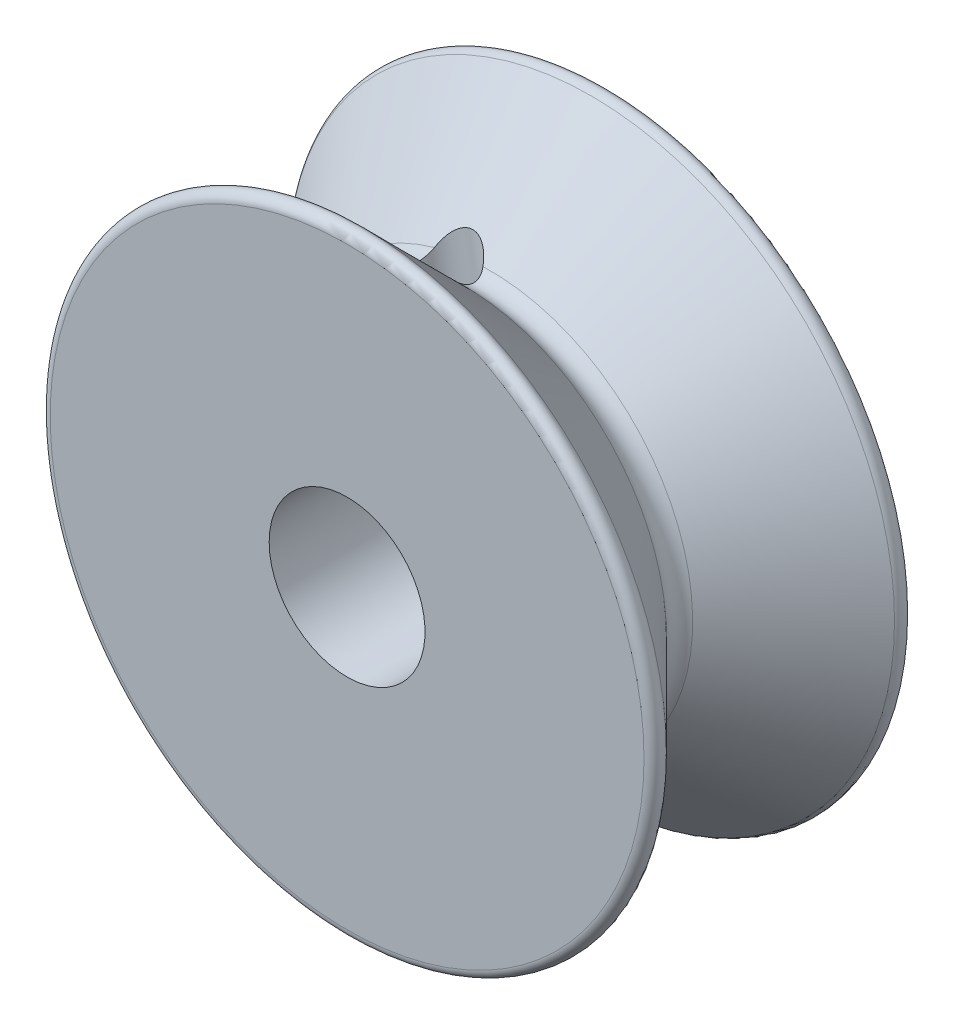
SolidWorks part; units mm, degrees
ref_plane "Front Plane" through (0, 0, 0) normal (0, 0, 1) x (1, 0, 0)
ref_plane "Top Plane" through (0, 0, 0) normal (0, 1, 0) x (1, 0, 0)
ref_plane "Right Plane" through (0, 0, 0) normal (1, 0, 0) x (0, 0, -1)
sketch "Sketch2" plane through (0, 0, 0) normal (0, 0, 1) x (1, 0, 0)
  line L0 (-0.3676, 7.7711) -> (0.0065, 8.0211)
  line L1 (0.0065, 8.0211) -> (0.3676, 7.7711)
  line L2 (0.3676, 7.7711) -> (0.8007, 7.8932)
  line L3 (0.8007, 7.8932) -> (1.0669, 7.5439)
  line L4 (1.0669, 7.5439) -> (1.5165, 7.5262)
  line L5 (1.5165, 7.5262) -> (1.6617, 7.1117)
  line L6 (1.6617, 7.1117) -> (2.0839, 6.956)
  line L7 (2.0839, 6.956) -> (2.0939, 6.5169)
  line L8 (2.0939, 6.5169) -> (2.4472, 6.2383)
  line L9 (2.4472, 6.2383) -> (2.3211, 5.8176)
  line L10 (2.3211, 5.8176) -> (2.5711, 5.4435)
  line L11 (2.5711, 5.4435) -> (2.3211, 5.0824)
  line L12 (2.3211, 5.0824) -> (2.4432, 4.6493)
  line L13 (2.4432, 4.6493) -> (2.0939, 4.3831)
  line L14 (2.0939, 4.3831) -> (2.0762, 3.9335)
  line L15 (2.0762, 3.9335) -> (1.6617, 3.7883)
  line L16 (1.6617, 3.7883) -> (1.506, 3.3661)
  line L17 (1.506, 3.3661) -> (1.0669, 3.3561)
  line L18 (1.0669, 3.3561) -> (0.7883, 3.0028)
  line L19 (0.7883, 3.0028) -> (0.3676, 3.1289)
  line L20 (0.3676, 3.1289) -> (-0.0065, 2.8789)
  line L21 (-0.0065, 2.8789) -> (-0.3676, 3.1289)
  line L22 (-0.3676, 3.1289) -> (-0.8007, 3.0068)
  line L23 (-0.8007, 3.0068) -> (-1.0669, 3.3561)
  line L24 (-1.0669, 3.3561) -> (-1.5165, 3.3738)
  line L25 (-1.5165, 3.3738) -> (-1.6617, 3.7883)
  line L26 (-1.6617, 3.7883) -> (-2.0839, 3.944)
  line L27 (-2.0839, 3.944) -> (-2.0939, 4.3831)
  line L28 (-2.0939, 4.3831) -> (-2.4472, 4.6617)
  line L29 (-2.4472, 4.6617) -> (-2.3211, 5.0824)
  line L30 (-2.3211, 5.0824) -> (-2.5711, 5.4565)
  line L31 (-2.5711, 5.4565) -> (-2.3211, 5.8176)
  line L32 (-2.3211, 5.8176) -> (-2.4432, 6.2507)
  line L33 (-2.4432, 6.2507) -> (-2.0939, 6.5169)
  line L34 (-2.0939, 6.5169) -> (-2.0762, 6.9665)
  line L35 (-2.0762, 6.9665) -> (-1.6617, 7.1117)
  line L36 (-1.6617, 7.1117) -> (-1.506, 7.5339)
  line L37 (-1.506, 7.5339) -> (-1.0669, 7.5439)
  line L38 (-1.0669, 7.5439) -> (-0.7883, 7.8972)
  line L39 (-0.7883, 7.8972) -> (-0.3676, 7.7711)
  line L40 (-0.3676, 7.7711) -> (0.3676, 7.7711) construction
  circle A1 centre (0, 5.45) radius 4
  circle A2 centre (0, 5.45) radius 2.35 construction
  point P68 (0, 5.45)
  dimension "D2" = 8
  dimension "D3" = 4.7
  dimension "D4" = 0.25
  dimension "D5" = 0.4392
  dimension "D6" = 5.1421
  dimension "D1" = 20
extrude "Boss-Extrude1" add sketch "Sketch2" against normal up to surface (2.9 mm away)
sketch "Sketch3" plane through (0, 0, 0) normal (0, 0, 1) x (1, 0, 0)
  circle A0 centre (0, 5.45) radius 3
  circle A1 centre (0, 5.45) radius 1.2
  dimension "D1" = 2.4
extrude "Boss-Extrude2" add sketch "Sketch3" along normal blind 2
ref_axis "Axis1" through (0, 5.45, 2) along (0, 0, -1)
ref_plane "Plane1" through (-0.8421, 5.3166, 0) normal (-0.1564, 0.9877, 0) x (0.9877, 0.1564, 0)
sketch "Sketch4" plane through (-0.8421, 5.3166, 0) normal (-0.1564, 0.9877, 0) x (0.9877, 0.1564, 0)
  line L0 (-3.1474, 1.6) -> (-7.1474, 1.6)
  line L1 (4.8526, 2.9) -> (-3.1474, 2.9) construction
  line L2 (-7.3242, 1.1732) -> (-4.6045, -1.5464)
  line L3 (-4.6045, -2.2536) -> (-7.3242, -4.9732)
  line L4 (-7.1474, -5.4) -> (-3.1474, -5.4)
  line L5 (-3.1474, -5.4) -> (-3.1474, 1.6)
  line L6 (-3.1474, 2.9) -> (-3.1474, 0) construction
  arc A0 (-4.6045, -1.5464) -> (-4.6045, -2.2536) centre (-4.9581, -1.9) cw
  arc A1 (-7.1474, 1.6) -> (-7.3242, 1.1732) centre (-7.1474, 1.35) ccw
  arc A2 (-7.3242, -4.9732) -> (-7.1474, -5.4) centre (-7.1474, -5.15) ccw
  point P12 (-6.1474, 0)
  dimension "D3" = 0.5
  dimension "D6" = 0.25
  dimension "D1" = 45
  dimension "D2" = 45
  dimension "D4" = 4
  dimension "D5" = 7
  dimension "D7" = 1.3
revolve "Revolve1" add sketch "Sketch4" angle 360 about axis through (0, 5.45, 2) along (0, 0, -1)
sketch "Sketch5" plane through (0, 0, 2) normal (0, 0, 1) x (1, 0, 0)
  circle A0 centre (0, 5.45) radius 2.1
  circle A1 centre (0, 5.45) radius 4
  dimension "D1" = 4.2
  dimension "D2" = 8
extrude "Boss-Extrude3" add sketch "Sketch5" along normal up to surface (3.4 mm away) up to face at (4, 5.45, 5.4)
sketch "Sketch7" plane through (-0.8421, 5.3166, 0) normal (-0.1564, 0.9877, 0) x (0.9877, 0.1564, 0)
  line L0 (0.8526, 1.1732) -> (0.8526, -4.9732) construction
  line L1 (9.0293, 1.1732) -> (-7.3242, 1.1732) construction
  line L2 (9.0293, -4.9732) -> (-7.3242, -4.9732) construction
  circle A0 centre (0.8526, -1.9) radius 0.75
  dimension "D1" = 1.5
extrude "Cut-Extrude1" cut sketch "Sketch7" against normal through all both and the other way through all
